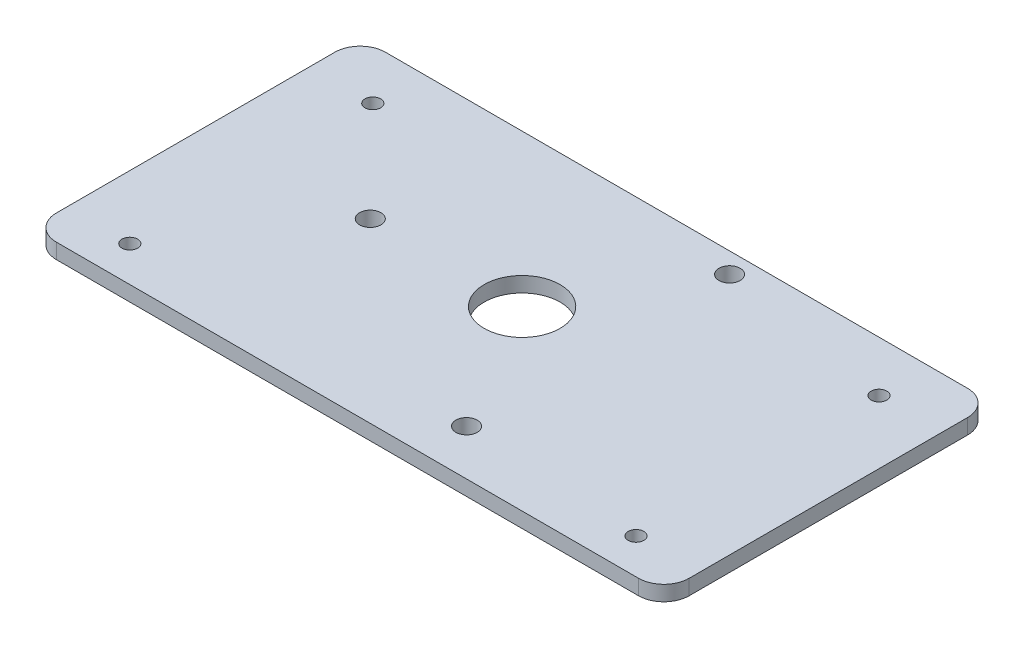
SolidWorks part; units mm, degrees
material "Thornel Mat VMA"
ref_plane "前视基准面" through (0, 0, 0) normal (0, 0, 1) x (1, 0, 0)
ref_plane "上视基准面" through (0, 0, 0) normal (0, 1, 0) x (1, 0, 0)
ref_plane "右视基准面" through (0, 0, 0) normal (1, 0, 0) x (0, 0, -1)
sketch "草图1" plane through (0, 0, 0) normal (0, 1, 0) x (1, 0, 0)
  line L1 (-62.5, 32.5) -> (62.5, 32.5)
  line L2 (-62.5, 32.5) -> (-62.5, -32.5)
  line L3 (-62.5, -32.5) -> (62.5, -32.5)
  line L4 (62.5, 32.5) -> (62.5, -32.5)
  line L5 (-62.5, 32.5) -> (62.5, -32.5) construction
  line L6 (-62.5, -32.5) -> (62.5, 32.5) construction
  point P0 (0, 0)
  dimension "D1" = 125
  dimension "D2" = 65
extrude "凸台-拉伸1" add sketch "草图1" along normal blind 3
ref_plane "基准面1" through (0, 0, 0) normal (0, -1, 0) x (-1, 0, 0)
sketch "草图2" plane through (0, 0, 0) normal (0, -1, 0) x (-1, 0, 0)
  line L0 (-14.5, 28.4808) -> (-14.5, -23.4808) construction
  line L1 (30.5, 2.5) -> (-14.5, 2.5) construction
  circle A0 centre (-50, 22.5) radius 1.55
  circle A1 centre (-50, -25.5) radius 1.55
  circle A2 centre (50, 22.5) radius 1.55
  circle A3 centre (50, -25.5) radius 1.55
  circle A4 centre (-14.5, -23.4808) radius 2.1
  circle A5 centre (-14.5, 28.4808) radius 2.1
  circle A6 centre (30.5, 2.5) radius 2.1
  circle A7 centre (0.5, 2.5) radius 30 construction
  circle A8 centre (0.5, 2.5) radius 7.5
  dimension "D1" = 15
extrude "切除-拉伸1" cut sketch "草图2" against normal blind 3
fillet "圆角1" radius 5 4 edges at (62.5, 1.5, 32.5) (-62.5, 1.5, 32.5) (62.5, 1.5, -32.5) (-62.5, 1.5, -32.5)
